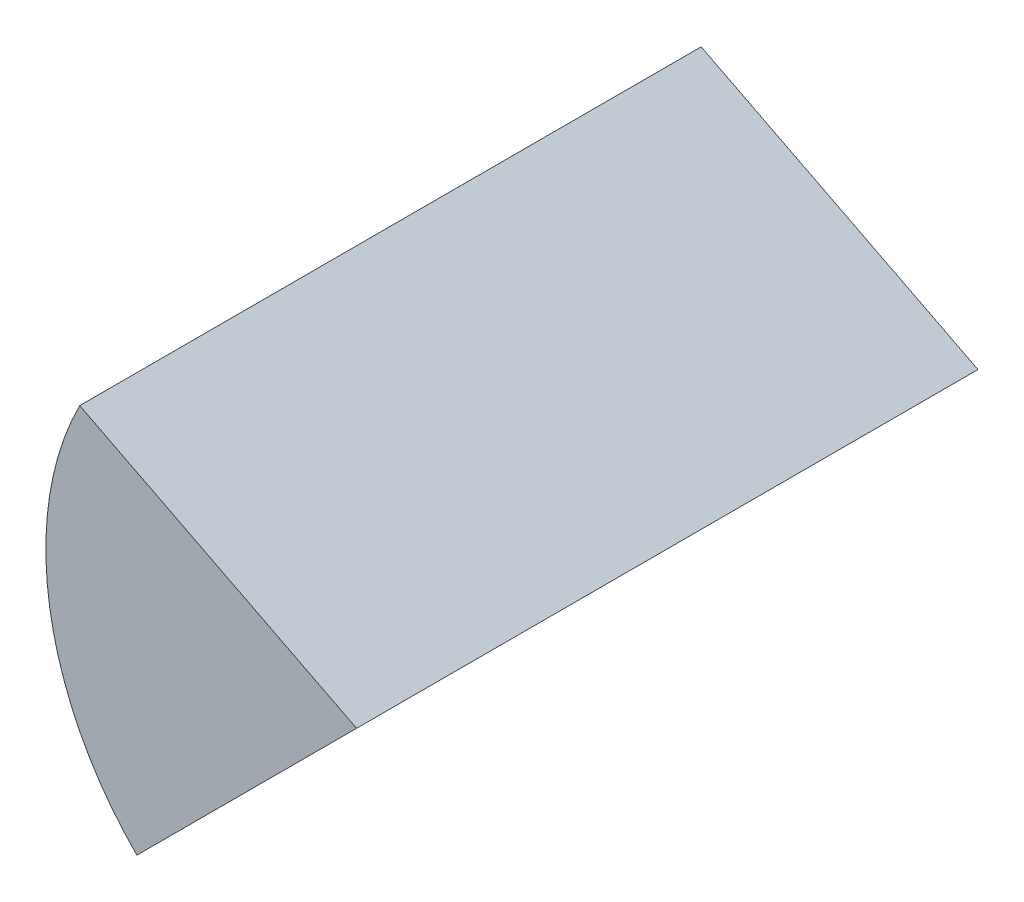
SolidWorks part; units mm, degrees
ref_plane "Alzado" through (0, 0, 0) normal (0, 0, 1) x (1, 0, 0)
ref_plane "Planta" through (0, 0, 0) normal (0, 1, 0) x (1, 0, 0)
ref_plane "Vista lateral" through (0, 0, 0) normal (1, 0, 0) x (0, 0, -1)
sketch "Croquis1" plane through (0, 0, 0) normal (0, 0, 1) x (1, 0, 0)
  line L2 (0, 0) -> (-22.2752, 11.3498)
  line L4 (0, 0) -> (-17.6777, -17.6777)
  arc A0 (-22.2752, 11.3498) -> (-17.6777, -17.6777) centre (0, 0) ccw
  dimension "D1" = 50
  dimension "D2" = 72
extrude "Saliente-Extruir1" add sketch "Croquis1" along normal blind 50
sketch "Croquis2" plane through (0, 0, 0) normal (0, 0, -1) x (-1, 0, 0)
  circle A0 centre (15.3096, -2.4793) radius 5
  dimension "D1" = 10
extrude "Cortar-Extruir1" cut sketch "Croquis2" against normal blind 10
